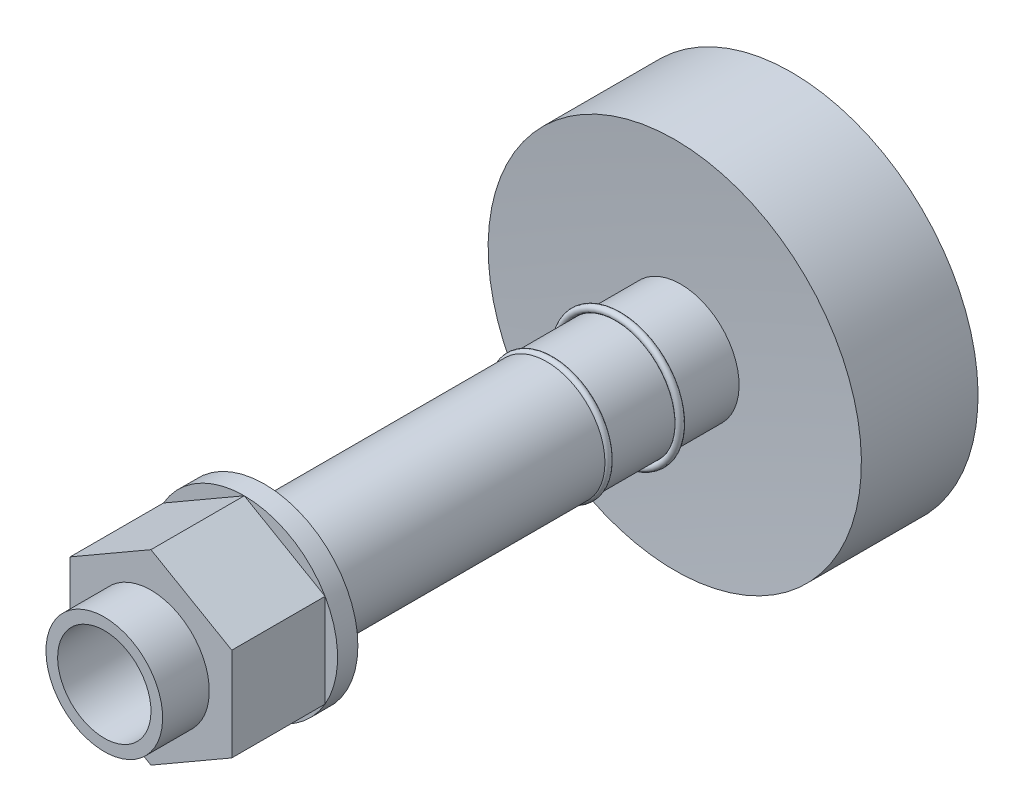
SolidWorks part; units mm, degrees
ref_plane "Front Plane" through (0, 0, 0) normal (0, 0, 1) x (1, 0, 0)
ref_plane "Top Plane" through (0, 0, 0) normal (0, 1, 0) x (1, 0, 0)
ref_plane "Right Plane" through (0, 0, 0) normal (1, 0, 0) x (0, 0, -1)
sketch "Sketch1" plane through (0, 0, 0) normal (1, 0, 0) x (0, 0, -1)
  line L0 (146.8504, 0) -> (-250, 0) construction
  line L1 (-127.6679, 20) -> (-127.6679, 40)
  line L2 (-127.6679, 40) -> (-78.9652, 40)
  line L4 (-77.6679, 25) -> (99.4321, 25)
  line L5 (146.8504, 20) -> (-127.6679, 20)
  line L6 (146.8504, 0.7536) -> (146.8504, 0)
  line L8 (146.8504, 80) -> (146.8504, 20)
  line L9 (146.8504, 0) -> (146.8504, 0.7536)
  line L11 (96.8504, 80) -> (146.8504, 80)
  line L14 (-127.6679, 25) -> (-147.6679, 25)
  line L15 (-147.6679, 25) -> (-147.6679, 20)
  line L16 (-147.6679, 20) -> (-127.6679, 20)
  line L18 (88, 0) -> (-88, 0) construction
  arc A0 (-77.6679, 25) -> (-78.9652, 40) centre (-1017.6797, -48.7435) ccw
  arc A2 (99.4321, 25) -> (96.8504, 80) centre (-1020.2888, 0) ccw
  circle A3 centre (-1020.2888, 0) radius 1120 construction
  point P19 (100.367, 25)
  point P20 (-2346.9029, -48.7435)
  point P21 (-2345.6715, -48.7435)
  point P22 (0, 0)
  point P25 (-704.6629, 0)
  point P26 (-1067.4513, 0)
  point P27 (-78.8271, 25)
  dimension "D7" = 1885.8
  dimension "D12" = 2240
  dimension "D2" = 25
  dimension "D3" = 80
  dimension "D4" = 40
  dimension "D5" = 20
  dimension "D1" = 50
  dimension "D8" = 20
  dimension "D9" = 177.1
  dimension "D6" = 50
  dimension "D11" = 48.7027
revolve "Revolve1" add sketch "Sketch1" angle 360 about L0
sketch "Sketch2" plane through (0, 0, 127.6679) normal (0, 0, 1) x (1, 0, 0)
  line L0 (0, 0) -> (38.5975, 0) construction
  line L1 (34.641, -20) -> (34.641, 20)
  line L2 (34.641, 20) -> (0, 40)
  line L3 (0, 40) -> (-34.641, 20)
  line L4 (-34.641, 20) -> (-34.641, -20)
  line L5 (-34.641, -20) -> (0, -40)
  line L6 (0, -40) -> (34.641, -20)
  line L7 (0, 0) -> (34.641, 20) construction
  circle A0 centre (0, 0) radius 34.641 construction
  circle A1 centre (0, 0) radius 47.4757
  dimension "D1" = 30
extrude "Cut-Extrude1" cut sketch "Sketch2" against normal blind 40
sketch "Sketch3" plane through (0, 0, 0) normal (0, 1, 0) x (1, 0, 0)
  line L0 (80, 96.8504) -> (-80, 96.8504) construction
  line L1 (25, 96.8504) -> (28, 96.8504)
  line L2 (25, 96.8504) -> (25, 98.8504)
  line L3 (25, 98.8504) -> (28, 98.8504)
  line L4 (28, 96.8504) -> (28, 98.8504)
  line L5 (25, -77.6679) -> (25, 99.4321) construction
  line L6 (0, 0) -> (0, 145.935) construction
  line L8 (25, 44.9306) -> (23, 44.9306)
  line L9 (25, 44.9306) -> (25, 41.9306)
  line L10 (25, 41.9306) -> (23, 41.9306)
  line L11 (23, 44.9306) -> (23, 41.9306)
  line L12 (25, -77.6679) -> (28, -77.6679)
  line L13 (25, -77.6679) -> (25, -79.6679)
  line L14 (25, -79.6679) -> (28, -79.6679)
  line L15 (28, -77.6679) -> (28, -79.6679)
  dimension "D1" = 2
  dimension "D2" = 3
  dimension "D3" = 2
  dimension "D4" = 3
  dimension "D5" = 2
  dimension "D6" = 3
revolve "Cut-Revolve1" cut sketch "Sketch3" angle 360 about L6
sketch "Sketch4" plane through (0, 0, 0) normal (0, 1, 0) x (1, 0, 0)
  line L0 (0, 154.6414) -> (0, -221.434) construction
  line L2 (19.9988, -90.7059) -> (21.9988, -90.7059)
  line L3 (19.9988, -90.7059) -> (19.9988, -93.7059)
  line L4 (19.9988, -93.7059) -> (21.9988, -93.7059)
  line L5 (21.9988, -90.7059) -> (21.9988, -93.7059)
  line L6 (19.9988, 87.725) -> (21.9988, 87.725)
  line L7 (19.9988, 87.725) -> (19.9988, 84.725)
  line L8 (19.9988, 84.725) -> (21.9988, 84.725)
  line L9 (21.9988, 87.725) -> (21.9988, 84.725)
  dimension "D1" = 2
  dimension "D2" = 3
  dimension "D3" = 2
  dimension "D4" = 3
revolve "Cut-Revolve2" cut sketch "Sketch4" angle 360 about L0
sketch "Sketch5" plane through (0, 0, 0) normal (0, 1, 0) x (1, 0, 0)
  line L0 (-28, 72.5089) -> (28, 72.5089) construction
  line L2 (0, 162.7228) -> (0, -163.8507) construction
  circle A0 centre (24.5, 43.4306) radius 1.5
  circle A1 centre (26.5032, 72.5089) radius 1.4649
  circle A2 centre (20.4923, 86.2421) radius 1.4
  circle A3 centre (26.5032, -77.2648) radius 1.4388
  circle A4 centre (20.4923, -92.2495) radius 1.4
  dimension "D1" = 2.8
  dimension "D2" = 2.8
revolve "Revolve2" add sketch "Sketch5" angle 360 about L2
equation "\"mountAngle\"=70.9702deg"
equation "\"ThrusterDim\"=160.5mm"
equation "\"hatchHoleDiameter\"=600mm"
equation "\"hullThickness\"=177.1mm"
equation "\"gasketHullInterconnectWidth\"=100mm"
equation "\"collarThickness\"=20mm"
equation "\"hatchTunnelLength\"=200mm"
equation "\"oRingDiameter\"=2mm"
equation "\"boltPatternRadiusInterconnect\"=500mm"
equation "\"interconnectBoltDiameter\"=30mm"
equation "\"hatchShaftDiameter\"=20mm"
equation "\"hatchMinima\"=39.9mm"
equation "\"hullDiameter\"=2240mm"
equation "\"hatchMaxima\"=180mm"
equation "\"bushingFlatHatch\"=15mm"
equation "\"hingePivotDiameter\"=20mm"
equation "\"handleWidth\"=250mm"
equation "\"handleHeight\"=160mm"
equation "\"handleThickness\"=25mm"
equation "\"FrameLength\"=2600mm"
equation "\"FrameMidLength\"=1800mm"
equation "\"TubeOD\"=100mm"
equation "\"FrameBackFlat\"=500mm"
equation "\"TubeWall\"=15.0001mm"
equation "\"TopMemberAngle\"=140deg"
equation "\"FrameHight\"=2500mm"
equation "\"D7@Sketch1\"=\"hullDiameter\" - \"hullThickness\" *2"
equation "\"D9@Sketch1\"=\"hullThickness\""
equation "\"D12@Sketch1\"=\"hullDiameter\""
